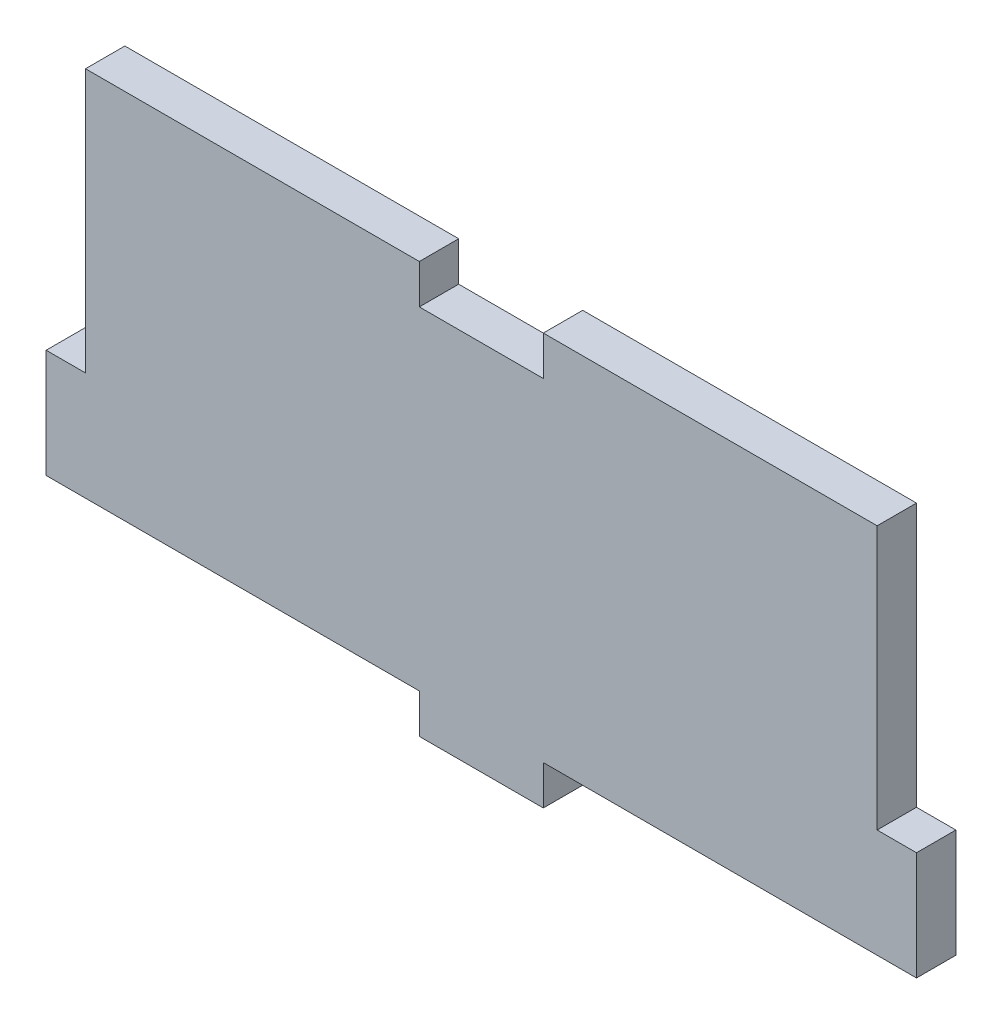
SolidWorks part; units mm, degrees
ref_plane "Front Plane" through (0, 0, 0) normal (0, 0, 1) x (1, 0, 0)
ref_plane "Top Plane" through (0, 0, 0) normal (0, 1, 0) x (1, 0, 0)
ref_plane "Right Plane" through (0, 0, 0) normal (1, 0, 0) x (0, 0, -1)
sketch "Sketch3" plane through (0, 0, 0) normal (0, 0, 1) x (1, 0, 0)
  line L0 (0, 0) -> (0, -60) construction
  line L1 (-127.7, 60) -> (127.7, 60)
  line L2 (-127.7, 60) -> (-127.7, -60)
  line L3 (-127.7, -60) -> (127.7, -60)
  line L4 (127.7, 60) -> (127.7, -60)
  line L5 (0, 0) -> (127.7, 0) construction
  line L6 (127.7, -25) -> (140.4, -25)
  line L7 (-20, -60) -> (20, -60)
  line L8 (-20, -60) -> (-20, -72.7)
  line L9 (-20, -72.7) -> (20, -72.7)
  line L10 (20, -60) -> (20, -72.7)
  line L11 (-127.7, -60) -> (-140.4, -60)
  line L12 (-127.7, -60) -> (-127.7, -25)
  line L13 (-127.7, -25) -> (-140.4, -25)
  line L14 (-140.4, -60) -> (-140.4, -25)
  line L15 (140.4, -60) -> (140.4, -25)
  line L16 (127.7, -60) -> (140.4, -60)
  line L17 (127.7, -60) -> (127.7, -25)
  point P18 (0, 0)
  dimension "D1" = 255.4
  dimension "D2" = 120
  dimension "D3" = 40
  dimension "D4" = 12.7
  dimension "D5" = 107.7
  dimension "D6" = 35
  dimension "D7" = 12.7
extrude "Boss-Extrude1" add sketch "Sketch3" along normal blind 12.7 contours L1 L4 L3 L2 | L9 L10 L7 L8 | L12 L11 L14 L13 | L17 L6 L15 L16
sketch "Sketch4" plane through (0, 0, 12.7) normal (0, 0, 1) x (1, 0, 0)
  line L0 (-127.7, 60) -> (127.7, 60) construction
  line L1 (-20, 60) -> (20, 60)
  line L2 (-20, 60) -> (-20, 47.3)
  line L3 (-20, 47.3) -> (20, 47.3)
  line L4 (20, 60) -> (20, 47.3)
  line L5 (20, -60) -> (20, -72.7) construction
  line L6 (-20, -60) -> (-20, -72.7) construction
  dimension "D1" = 12.7
extrude "Cut-Extrude1" cut sketch "Sketch4" against normal blind 12.7
